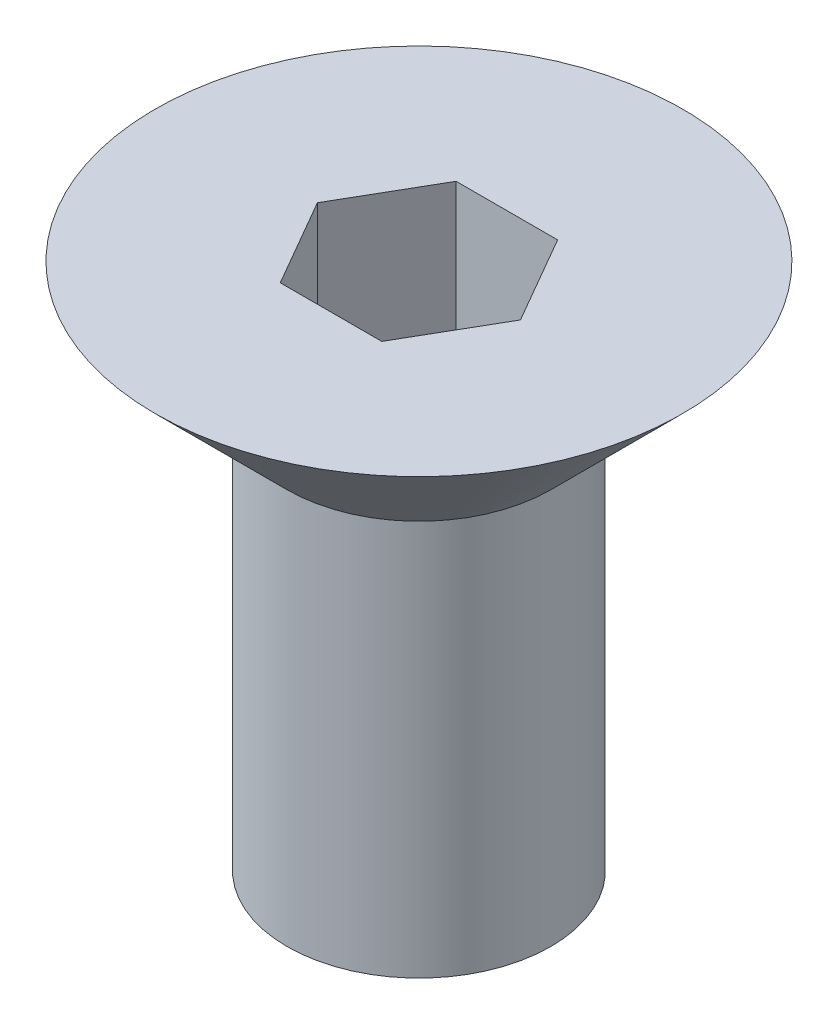
SolidWorks part; units mm, degrees
material "AISI 304"
ref_plane "Front Plane" through (0, 0, 0) normal (0, 0, 1) x (1, 0, 0)
ref_plane "Top Plane" through (0, 0, 0) normal (0, 1, 0) x (1, 0, 0)
ref_plane "Right Plane" through (0, 0, 0) normal (1, 0, 0) x (0, 0, -1)
sketch "Sketch1" plane through (0, 0, 0) normal (0, 0, 1) x (1, 0, 0)
  line L0 (0, 61.6916) -> (0, -59.3578) construction
  line L1 (0, -6) -> (1.5, -6)
  line L2 (1.5, -6) -> (1.5, -1.5)
  line L3 (-3.1135, 0.1135) -> (-1.5, -1.5) construction
  line L5 (3, 0) -> (0, 0)
  line L6 (0, 0) -> (0, -6)
  line L7 (1.5, -1.5) -> (3, 0)
  dimension "D1" = 90
  dimension "D2" = 6
  dimension "D3" = 3
  dimension "D5" = 6
revolve "Revolve1" add sketch "Sketch1" angle 360 about L0
sketch "Sketch2" plane through (0, 0, 0) normal (0, 1, 0) x (-1, 0, 0)
  line L1 (-0.5774, -1) -> (0.5774, -1)
  line L2 (0.5774, -1) -> (1.1547, 0)
  line L3 (1.1547, 0) -> (0.5774, 1)
  line L4 (0.5774, 1) -> (-0.5774, 1)
  line L5 (-0.5774, 1) -> (-1.1547, 0)
  line L6 (-1.1547, 0) -> (-0.5774, -1)
  circle A0 centre (0, 0) radius 1 construction
  dimension "D1" = 2
extrude "Cut-Extrude1" cut sketch "Sketch2" against normal blind 1.5
